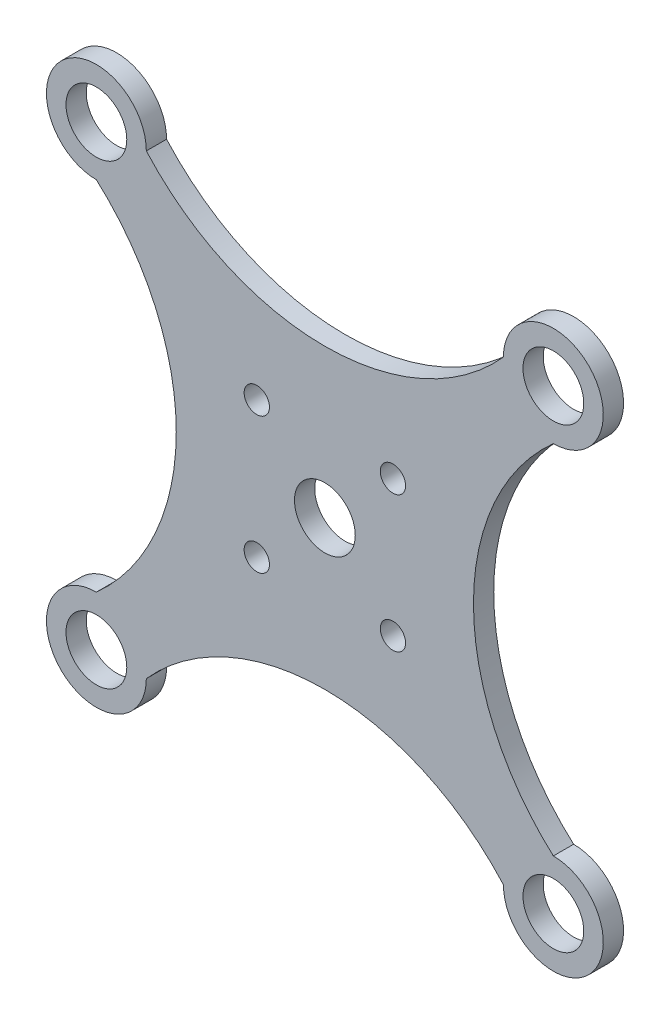
SolidWorks part; units mm, degrees
material "Thornel Mat VMA"
ref_plane "Alzado" through (0, 0, 0) normal (0, 0, 1) x (1, 0, 0)
ref_plane "Planta" through (0, 0, 0) normal (0, 1, 0) x (1, 0, 0)
ref_plane "Vista lateral" through (0, 0, 0) normal (1, 0, 0) x (0, 0, -1)
sketch "Croquis1" plane through (0, 0, 0) normal (0, 0, 1) x (1, 0, 0)
  line L0 (17.5, 0) -> (27.5, 0) construction
  line L1 (-27.5, -27.5) -> (27.5, -27.5)
  line L2 (-27.5, -27.5) -> (-27.5, 27.5)
  line L3 (-27.5, 27.5) -> (27.5, 27.5)
  line L4 (27.5, -27.5) -> (27.5, 27.5)
  line L5 (-27.5, -27.5) -> (27.5, 27.5) construction
  line L6 (-27.5, 27.5) -> (27.5, -27.5) construction
  line L7 (0, 17.5) -> (0, 27.5) construction
  circle A0 centre (0, 0) radius 17.5 construction
  circle A5 centre (-22.5503, 22.5503) radius 3
  circle A6 centre (22.5503, 22.5503) radius 3
  circle A7 centre (22.5503, -22.5503) radius 3
  circle A8 centre (-22.5503, -22.5503) radius 3
  circle A9 centre (0, 0) radius 3
  circle A10 centre (0, 0) radius 9.5 construction
  circle A11 centre (-6.7175, 6.7175) radius 1.25
  circle A12 centre (6.7175, 6.7175) radius 1.25
  circle A13 centre (6.7175, -6.7175) radius 1.25
  circle A14 centre (-6.7175, -6.7175) radius 1.25
  point P0 (0, 0)
  point P16 (0, 0)
  point P17 (-6.7175, 6.7175)
  point P21 (0, 0)
  point P32 (0, 0)
  point P35 (0, 0)
  dimension "D1" = 35
  dimension "D2" = 19
  dimension "D6" = 6
  dimension "D9" = 55
  dimension "D3" = 2.5
  dimension "D5" = 10
  dimension "D8" = 7
  dimension "D7" = 4
  dimension "D4" = 4
extrude "Saliente-Extruir1" add sketch "Croquis1" along normal blind 2
fillet "Redondeo1" radius 5 4 edges at (27.5, 27.5, 1) (27.5, -27.5, 1) (-27.5, -27.5, 1) (-27.5, 27.5, 1)
sketch "Croquis2" plane through (0, 0, 2) normal (0, 0, 1) x (1, 0, 0)
  arc A0 (-22.5503, -17.6213) -> (-17.6213, -22.5503) centre (-22.5503, -22.5503) ccw
  circle A1 centre (22.5503, -22.5503) radius 4.9289 construction
  arc A2 (-17.6213, -22.5503) -> (17.6213, -22.5503) centre (0, -38.2989) cw
  arc A3 (-17.6213, 22.5503) -> (-22.5503, 17.6213) centre (-22.5503, 22.5503) ccw
  arc A4 (-22.5503, 17.6213) -> (-22.5503, -17.6213) centre (-38.2989, 0) cw
  arc A5 (22.5503, 17.6213) -> (17.6213, 22.5503) centre (22.5503, 22.5503) ccw
  arc A6 (17.6213, 22.5503) -> (-17.6213, 22.5503) centre (0, 38.2989) cw
  arc A7 (17.6213, -22.5503) -> (22.5503, -17.6213) centre (22.5503, -22.5503) ccw
  arc A8 (22.5503, -17.6213) -> (22.5503, 17.6213) centre (38.2989, 0) cw
  circle A10 centre (-22.5503, -22.5503) radius 3 construction
  circle A11 centre (-22.5503, 22.5503) radius 3 construction
  point P27 (0, 0)
  line M10 (27.5, -22.5) -> (27.5, 22.5)
  arc M11 (27.5, 22.5) -> (22.5, 27.5) centre (22.5, 22.5) ccw
  line M12 (22.5, 27.5) -> (-22.5, 27.5)
  arc M13 (-22.5, 27.5) -> (-27.5, 22.5) centre (-22.5, 22.5) ccw
  line M14 (-27.5, 22.5) -> (-27.5, -22.5)
  arc M15 (-27.5, -22.5) -> (-22.5, -27.5) centre (-22.5, -22.5) ccw
  line M16 (-22.5, -27.5) -> (22.5, -27.5)
  arc M17 (22.5, -27.5) -> (27.5, -22.5) centre (22.5, -22.5) ccw
  dimension "D2" = 1.9289
  dimension "D1" = 4
extrude "Cortar-Extruir1" cut sketch "Croquis2" against normal blind 2 contours A4 A3 A0 M13 M14 M15 | A6 A5 A3 M11 M12 M13 | A8 A7 A5 M17 M10 M11 | A7 A2 A0 M15 M16 M17
